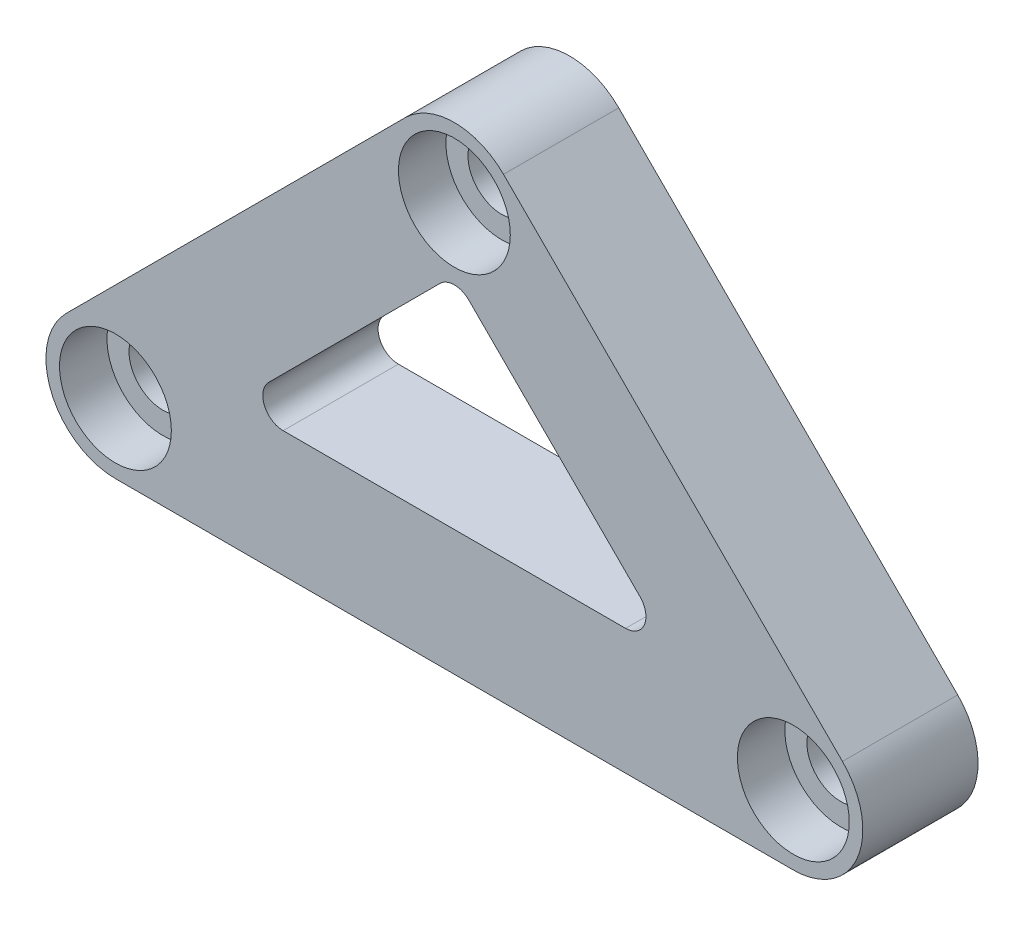
SolidWorks part; units mm, degrees
ref_plane "Front Plane" through (0, 0, 0) normal (0, 0, 1) x (1, 0, 0)
ref_plane "Top Plane" through (0, 0, 0) normal (0, 1, 0) x (1, 0, 0)
ref_plane "Right Plane" through (0, 0, 0) normal (1, 0, 0) x (0, 0, -1)
sketch "Sketch2" plane through (0, 0, 0) normal (0, 0, 1) x (1, 0, 0)
  line L0 (-100, 0) -> (0, 0) construction
  line L1 (-100, 10.25) -> (0, 10.25)
  line L2 (-100, -10.25) -> (0, -10.25)
  line L3 (0, 0) -> (-50, 50) construction
  line L4 (-7.2478, -7.2478) -> (-57.2478, 42.7522)
  line L5 (7.2478, 7.2478) -> (-42.7522, 57.2478)
  line L6 (-100, 0) -> (-50, 50) construction
  line L7 (-107.2478, 7.2478) -> (-57.2478, 57.2478)
  line L8 (-92.7522, -7.2478) -> (-42.7522, 42.7522)
  arc A0 (-100, 10.25) -> (-100, -10.25) centre (-100, 0) ccw
  arc A1 (0, -10.25) -> (0, 10.25) centre (0, 0) ccw
  arc A2 (-7.2478, -7.2478) -> (7.2478, 7.2478) centre (0, 0) ccw
  arc A3 (-42.7522, 57.2478) -> (-57.2478, 42.7522) centre (-50, 50) ccw
  arc A4 (-107.2478, 7.2478) -> (-92.7522, -7.2478) centre (-100, 0) ccw
  arc A5 (-42.7522, 42.7522) -> (-57.2478, 57.2478) centre (-50, 50) ccw
  point P3 (-50, 0)
  point P8 (-25, 25)
  point P15 (-75, 25)
  dimension "D1" = 100
  dimension "D2" = 20.5
  dimension "D3" = 45
  dimension "D4" = 45
extrude "Boss-Extrude4" add sketch "Sketch2" along normal blind 17 contours A4 L2 A2 L4 L1 L8 | A0 A4 L8 L1 | A3 L7 A0 L1 L8 L4 | L8 A5 A3 L4 | A5 L8 L4 L1 A1 L5 | L4 A2 A1 L1
sketch "Sketch3" plane through (0, 0, 0) normal (0, 0, -1) x (-1, 0, 0)
  line L0 (57.2478, 57.2478) -> (107.2478, 7.2478)
  line L1 (57.2478, 57.2478) -> (107.2478, 7.2478)
  line L2 (100, -10.25) -> (0, -10.25)
  line L3 (100, -10.25) -> (0, -10.25)
  line L4 (-7.2478, 7.2478) -> (42.7522, 57.2478)
  line L5 (-7.2478, 7.2478) -> (42.7522, 57.2478)
  circle A0 centre (0, 0) radius 8.25
  circle A1 centre (50, 50) radius 8.25
  circle A2 centre (100, 0) radius 8.25
  arc A3 (100, -10.25) -> (107.2478, 7.2478) centre (100, 0) ccw
  arc A4 (100, -10.25) -> (107.2478, 7.2478) centre (100, 0) ccw
  arc A5 (-7.2478, 7.2478) -> (0, -10.25) centre (0, 0) ccw
  arc A6 (-7.2478, 7.2478) -> (0, -10.25) centre (0, 0) ccw
  arc A7 (57.2478, 57.2478) -> (42.7522, 57.2478) centre (50, 50) ccw
  arc A8 (57.2478, 57.2478) -> (42.7522, 57.2478) centre (50, 50) ccw
  dimension "D1" = 16.5
  dimension "D2" = 16.5
  dimension "D3" = 16.5
extrude "Cut-Extrude1" cut sketch "Sketch3" against normal blind 7 contours A0 | A1 | A2
sketch "Sketch4" plane through (0, 0, 17) normal (0, 0, 1) x (1, 0, 0)
  circle A0 centre (-100, 0) radius 8.25
  circle A1 centre (-50, 50) radius 8.25
  circle A2 centre (0, 0) radius 8.25
  arc A3 (-107.2478, 7.2478) -> (-100, -10.25) centre (-100, 0) ccw construction
  arc A4 (-42.7522, 57.2478) -> (-57.2478, 57.2478) centre (-50, 50) ccw construction
  arc A5 (0, -10.25) -> (7.2478, 7.2478) centre (0, 0) ccw construction
  dimension "D1" = 16.5
  dimension "D2" = 16.5
  dimension "D3" = 16.5
extrude "Cut-Extrude2" cut sketch "Sketch4" against normal blind 7
sketch "Sketch5" plane through (0, 0, 0) normal (0, 0, -1) x (-1, 0, 0)
  line L2 (17.5, 8.25) -> (50, 40.75)
  line L3 (50, 40.75) -> (82.5, 8.25)
  line L4 (82.5, 8.25) -> (17.5, 8.25)
  circle A0 centre (0, 0) radius 8.25 construction
  circle A2 centre (50, 50) radius 8.25 construction
  dimension "D3" = 45
  dimension "D1" = 9.25
  dimension "D2" = 45
extrude "Cut-Extrude3" cut sketch "Sketch5" against normal through all
sketch "Sketch6" plane through (0, 0, 17) normal (0, 0, 1) x (1, 0, 0)
  circle A1 centre (-100, 0) radius 5
  circle A2 centre (-50, 50) radius 5
  circle A3 centre (0, 0) radius 5
  circle A4 centre (-100, 0) radius 8.25 construction
  circle A6 centre (-50, 50) radius 8.25 construction
  circle A7 centre (0, 0) radius 8.25 construction
  dimension "D1" = 10
  dimension "D2" = 10
  dimension "D3" = 10
extrude "Cut-Extrude4" cut sketch "Sketch6" against normal blind 16.6
fillet "Fillet1" radius 3 3 edges at (-82.5, 8.25, 8.5) (-17.5, 8.25, 8.5) (-50, 40.75, 8.5)
equation "\"D4@Sketch2\"=\"D3@Sketch2\""
equation "\"D2@Sketch3\"=\"D1@Sketch3\""
equation "\"D3@Sketch3\"=\"D1@Sketch3\""
equation "\"D2@Sketch4\"=\"D1@Sketch4\""
equation "\"D3@Sketch4\"=\"D1@Sketch4\""
equation "\"D3@Sketch5\"=\"D2@Sketch5\""
equation "\"D2@Sketch6\"=\"D1@Sketch6\""
equation "\"D3@Sketch6\"=\"D2@Sketch6\""
